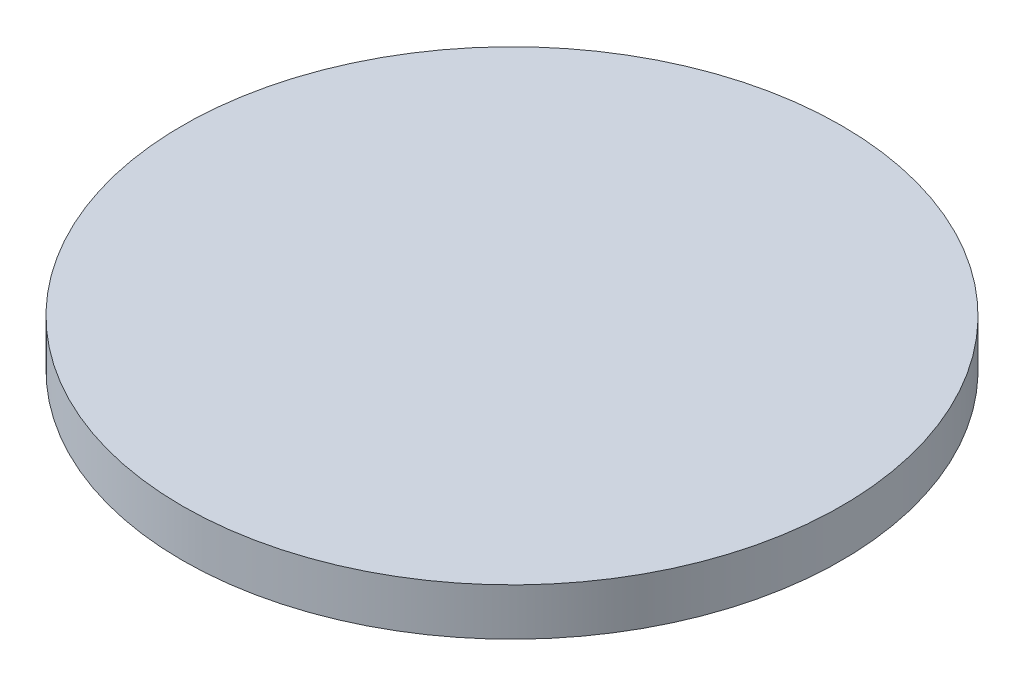
SolidWorks part; units mm, degrees
material "Żeliwo szare"
ref_plane "Płaszczyzna przednia" through (0, 0, 0) normal (0, 0, 1) x (1, 0, 0)
ref_plane "Płaszczyzna górna" through (0, 0, 0) normal (0, 1, 0) x (1, 0, 0)
ref_plane "Płaszczyzna prawa" through (0, 0, 0) normal (1, 0, 0) x (0, 0, -1)
sketch "Szkic1" plane through (0, 0, 0) normal (0, 1, 0) x (1, 0, 0)
  circle A0 centre (0, 0) radius 140
  dimension "D1" = 280
extrude "Dodanie-wyciągnięcie1" add sketch "Szkic1" along normal blind 20
